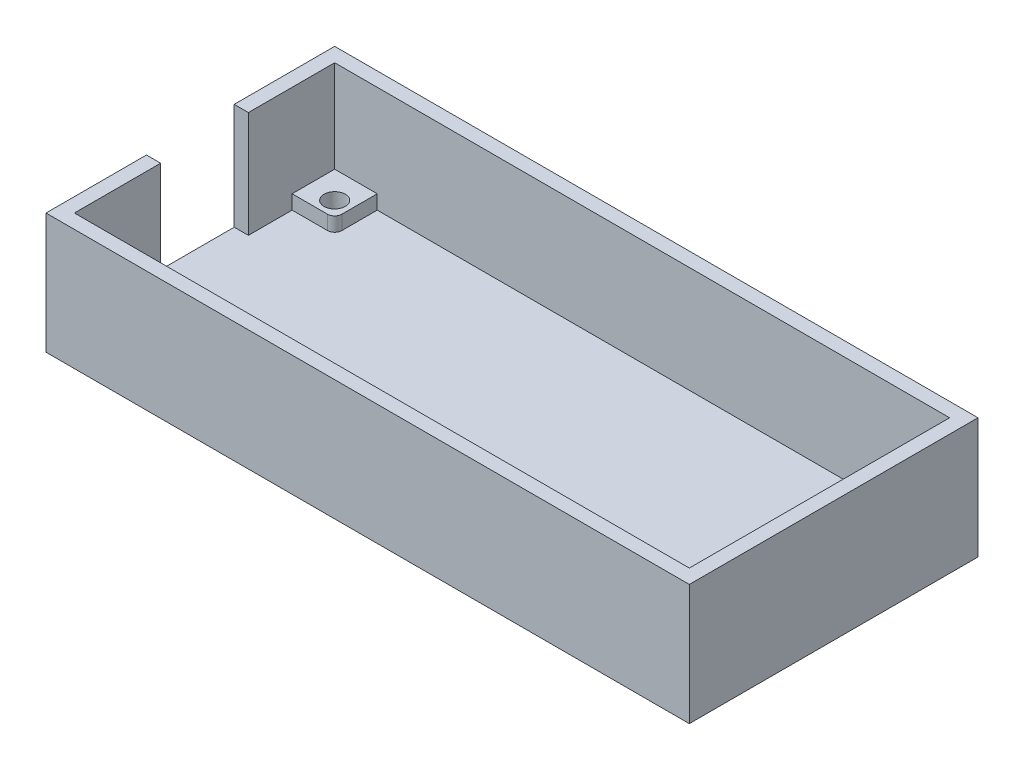
SolidWorks part; units mm, degrees
ref_plane "Front Plane" through (0, 0, 0) normal (0, 0, 1) x (1, 0, 0)
ref_plane "Top Plane" through (0, 0, 0) normal (0, 1, 0) x (1, 0, 0)
ref_plane "Right Plane" through (0, 0, 0) normal (1, 0, 0) x (0, 0, -1)
sketch "Sketch1" plane through (0, 0, 0) normal (0, 1, 0) x (1, 0, 0)
  line L1 (-45.35, 20.35) -> (45.35, 20.35)
  line L2 (-45.35, 20.35) -> (-45.35, -20.35)
  line L3 (-45.35, -20.35) -> (45.35, -20.35)
  line L4 (45.35, 20.35) -> (45.35, -20.35)
  line L5 (-45.35, 20.35) -> (45.35, -20.35) construction
  line L6 (-45.35, -20.35) -> (45.35, 20.35) construction
  circle A0 centre (-39.55, 14.55) radius 1.5
  circle A1 centre (39.55, 14.55) radius 1.5
  circle A2 centre (-39.55, -14.55) radius 1.5
  circle A3 centre (39.55, -14.55) radius 1.5
  point P0 (0, 0)
  dimension "D4" = 14.55
  dimension "D3" = 39.55
  dimension "D7" = 3
  dimension "D8" = 79.1
  dimension "D1" = 40.7
  dimension "D2" = 90.7
  dimension "D9" = 29.1
  dimension "D5" = 2
  dimension "D6" = 2
extrude "Boss-Extrude3" add sketch "Sketch1" along normal blind 2
sketch "Sketch2" plane through (0, 2, 0) normal (0, 1, 0) x (1, 0, 0)
  line L4 (-45.35, -20.35) -> (45.35, -20.35) construction
  line L5 (45.35, -20.35) -> (45.35, 20.35) construction
  line L6 (45.35, 20.35) -> (-45.35, 20.35) construction
  line L7 (-45.35, 20.35) -> (-45.35, -20.35) construction
  line L8 (43.35, -18.35) -> (43.35, 18.35)
  line L9 (43.35, 18.35) -> (-43.35, 18.35)
  line L10 (-43.35, 18.35) -> (-43.35, -18.35)
  line L11 (-43.35, -18.35) -> (43.35, -18.35)
  line L12 (43.35, -18.35) -> (43.35, 18.35)
  line L13 (43.35, 18.35) -> (-43.35, 18.35)
  line L14 (-43.35, 18.35) -> (-43.35, -18.35)
  line L15 (-43.35, -18.35) -> (43.35, -18.35)
  line L16 (-45.35, -20.35) -> (45.35, -20.35)
  line L17 (45.35, -20.35) -> (45.35, 20.35)
  line L18 (45.35, 20.35) -> (-45.35, 20.35)
  line L19 (-45.35, 20.35) -> (-45.35, -20.35)
  dimension "D1" = 2
extrude "Boss-Extrude4" add sketch "Sketch2" along normal blind 15
sketch "Cutout\\" plane through (-45.35, 0, 0) normal (-1, 0, 0) x (0, 0, 1)
  line L0 (-20.35, 0) -> (20.35, 0) construction
  line L1 (-20.35, 17) -> (20.35, 17) construction
  line L3 (6.1847, 2) -> (-6.1847, 2)
  line L4 (6.1847, 2) -> (6.1847, 17)
  line L5 (6.1847, 17) -> (-6.1847, 17)
  line L6 (-6.1847, 2) -> (-6.1847, 17)
  dimension "D1" = 6.5
  dimension "D2" = 6.5
  dimension "D3" = 2
extrude "Cut-Extrude1" cut sketch "Cutout\\" against normal up to next
sketch "Sketch3" plane through (0, 2, 0) normal (0, 1, 0) x (1, 0, 0)
  line L0 (-43.35, 12.35) -> (-38.35, 12.35)
  line L1 (-43.35, 18.35) -> (-43.35, 6.1847) construction
  line L2 (-37.35, 13.35) -> (-37.35, 18.35)
  line L3 (43.35, 18.35) -> (-43.35, 18.35) construction
  line L4 (43.35, 18.35) -> (-43.35, 18.35) construction
  line L5 (-43.35, 18.35) -> (-43.35, 6.1847) construction
  line L6 (-37.35, 18.35) -> (-43.35, 18.35)
  line L7 (-43.35, 18.35) -> (-43.35, 12.35)
  circle A0 centre (-39.55, 14.55) radius 1.5 construction
  circle A1 centre (-39.55, 14.55) radius 1.5
  arc A2 (-38.35, 12.35) -> (-37.35, 13.35) centre (-38.35, 13.35) ccw
  point P12 (-37.35, 12.35)
  dimension "D3" = 1
  dimension "D1" = 6
  dimension "D2" = 6
extrude "Boss-Extrude5" add sketch "Sketch3" along normal blind 2
mirror "Mirror1" about plane through (0, 0, 0) normal (1, 0, 0) of "Boss-Extrude5"
mirror "Mirror2" about plane through (0, 0, 0) normal (0, 0, 1) of "Mirror1", "Boss-Extrude5"
